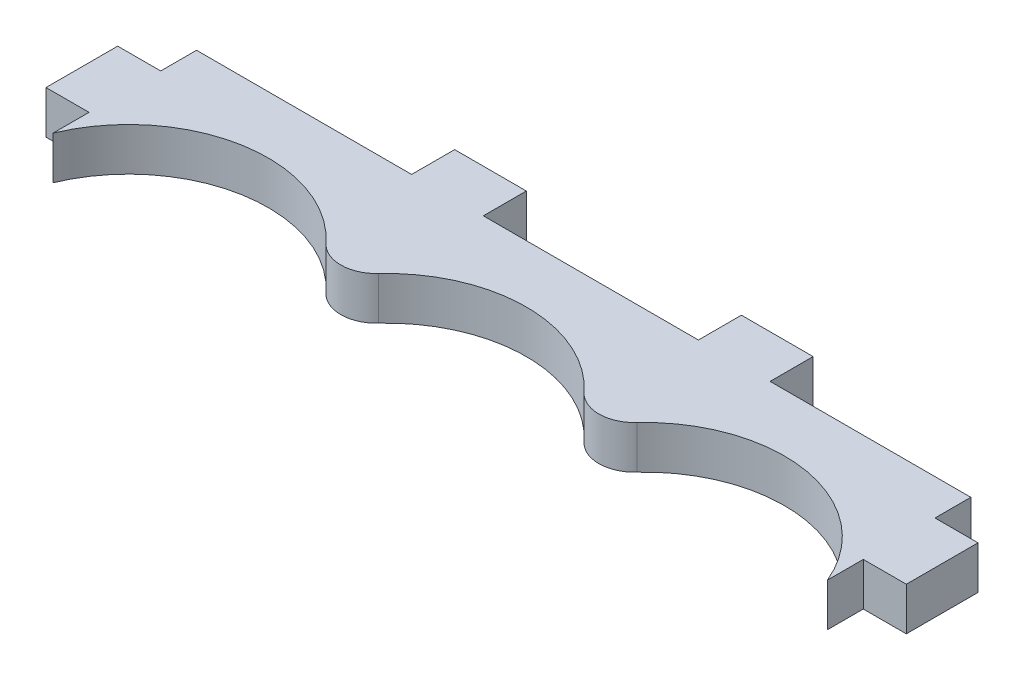
SolidWorks part; units mm, degrees
ref_plane "Front Plane" through (0, 0, 0) normal (0, 0, 1) x (1, 0, 0)
ref_plane "Top Plane" through (0, 0, 0) normal (0, 1, 0) x (1, 0, 0)
ref_plane "Right Plane" through (0, 0, 0) normal (1, 0, 0) x (0, 0, -1)
sketch "Sketch1" plane through (0, 0, 0) normal (0, 1, 0) x (1, 0, 0)
  line L0 (30, 0) -> (40, 0) construction
  line L1 (0, 0) -> (30, 0)
  line L2 (0, 0) -> (0, -5)
  line L3 (0, -20) -> (36, -20) construction
  line L4 (108, 0) -> (108, -5)
  line L5 (40, 0) -> (70, 0)
  line L6 (70, 0) -> (80, 0) construction
  line L7 (80, 0) -> (108, 0)
  line L8 (0, -5) -> (0, -15) construction
  line L9 (0, -15) -> (0, -20)
  line L10 (108, -5) -> (108, -15) construction
  line L11 (108, -15) -> (108, -20)
  line L12 (-66.8112, 6) -> (40, 6) construction
  line L13 (30, 0) -> (30, 6)
  line L14 (30, 6) -> (40, 6)
  line L15 (40, 6) -> (40, 0)
  line L16 (70, 0) -> (70, 6)
  line L17 (70, 6) -> (80, 6)
  line L18 (80, 6) -> (80, 0)
  line L19 (0, -8) -> (108, -8) construction
  line L20 (114, 0) -> (114, -20) construction
  line L21 (0, -5) -> (-6, -5)
  line L22 (-6, -5) -> (-6, -15)
  line L23 (-6, -15) -> (0, -15)
  line L24 (108, -5) -> (114, -5)
  line L25 (114, -5) -> (114, -15)
  line L26 (114, -15) -> (108, -15)
  line L27 (36, -20) -> (72, -20) construction
  line L28 (72, -20) -> (108, -20) construction
  arc A0 (0, -20) -> (36, -20) centre (18, -27.5) cw
  arc A1 (36, -20) -> (72, -20) centre (54, -27.5) cw
  arc A2 (72, -20) -> (108, -20) centre (90, -27.5) cw
  dimension "D1" = 108
  dimension "D2" = 20
  dimension "D3" = 10
  dimension "D4" = 10
  dimension "D5" = 30
  dimension "D6" = 30
  dimension "D7" = 6
  dimension "D8" = 6
  dimension "D9" = 10
  dimension "D10" = 5
  dimension "D11" = 12
extrude "Boss-Extrude1" add sketch "Sketch1" along normal blind 6
fillet "Fillet1" radius 5 2 edges at (72, 3, 20) (36, 3, 20)
